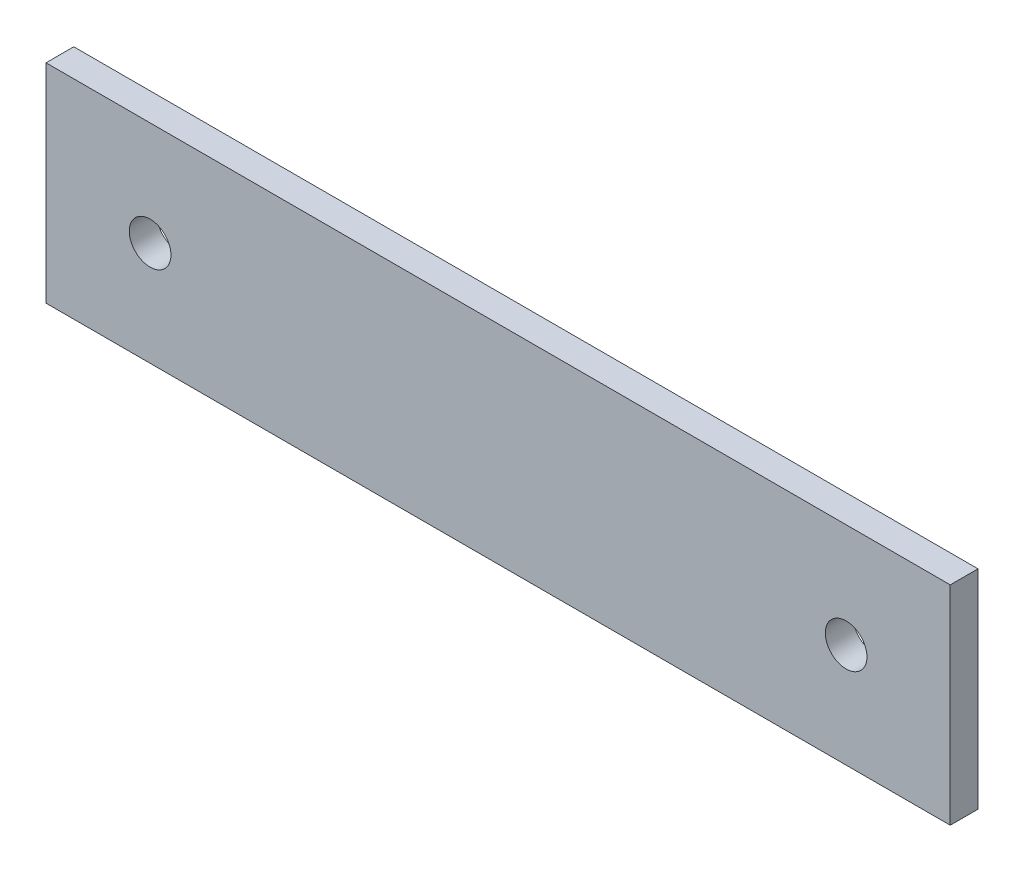
SolidWorks part; units mm, degrees
ref_plane "前视基准面" through (0, 0, 0) normal (0, 0, 1) x (1, 0, 0)
ref_plane "上视基准面" through (0, 0, 0) normal (0, 1, 0) x (1, 0, 0)
ref_plane "右视基准面" through (0, 0, 0) normal (1, 0, 0) x (0, 0, -1)
other "Configuration Table"
sketch "草图1" plane through (0, 0, 0) normal (0, 0, 1) x (1, 0, 0)
  line L1 (-15, -15) -> (115.3, -15)
  line L2 (-15, -15) -> (-15, 15)
  line L3 (-15, 15) -> (115.3, 15)
  line L4 (115.3, -15) -> (115.3, 15)
  line L5 (-15, -15) -> (115.3, 15) construction
  line L6 (-15, 15) -> (115.3, -15) construction
  circle A0 centre (0, 0) radius 3
  circle A1 centre (100.3, 0) radius 3
  point P0 (50.15, 0)
extrude "凸台-拉伸1" add sketch "草图1" along normal mid plane 4
